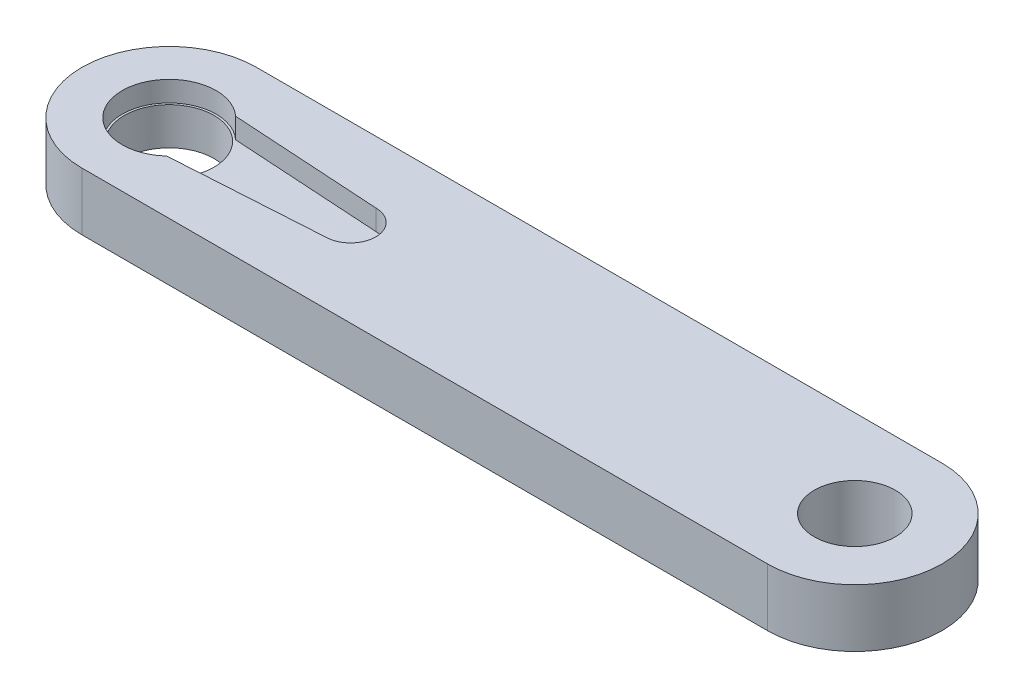
SolidWorks part; units mm, degrees
ref_plane "Front Plane" through (0, 0, 0) normal (0, 0, 1) x (1, 0, 0)
ref_plane "Top Plane" through (0, 0, 0) normal (0, 1, 0) x (1, 0, 0)
ref_plane "Right Plane" through (0, 0, 0) normal (1, 0, 0) x (0, 0, -1)
sketch "Sketch1" plane through (0, 0, 0) normal (0, 1, 0) x (1, 0, 0)
  line L0 (0, 0) -> (62, 0) construction
  line L1 (0, 7) -> (55, 7)
  line L2 (0, -7) -> (55, -7)
  arc A0 (0, 7) -> (0, -7) centre (0, 0) ccw
  arc A2 (55, -7) -> (55, 7) centre (55, 0) ccw
  point P11 (62, 0)
  dimension "D1" = 7
  dimension "D2" = 62
extrude "Boss-Extrude1" add sketch "Sketch1" along normal blind 3
sketch "Sketch2" plane through (0, 0, 0) normal (0, -1, 0) x (1, 0, 0)
  circle A0 centre (0, 0) radius 3.6
  dimension "D1" = 7.2
extrude "Cut-Extrude1" cut sketch "Sketch2" against normal blind 3.95
sketch "Sketch3" plane through (0, 3, 0) normal (0, 1, 0) x (1, 0, 0)
  line L0 (2.49, 2.6) -> (2.49, -2.6) construction
  line L1 (3.6, 0) -> (16.4, 0) construction
  line L2 (2.49, -2.6) -> (14.55, -1.85) construction
  line L3 (14.55, -1.85) -> (14.55, 1.85) construction
  line L4 (14.55, 1.85) -> (2.49, 2.6) construction
  line L5 (14.5554, 2.02) -> (2.5618, 2.7659)
  line L6 (2.5618, -2.7659) -> (14.5554, -2.02)
  line L11 (0, -7) -> (55, -7)
  line L12 (55, 7) -> (0, 7)
  line L13 (0, -7) -> (55, -7)
  line L14 (55, 7) -> (0, 7)
  arc A1 (14.55, -1.85) -> (14.55, 1.85) centre (14.55, 0) ccw construction
  circle A2 centre (0, 0) radius 3.6 construction
  circle A3 centre (14.55, 0) radius 1.85 construction
  circle A4 centre (0, 0) radius 3.575 construction
  arc A5 (2.49, -2.6) -> (2.49, 2.6) centre (0, 0) cw construction
  arc A7 (2.5618, -2.7659) -> (2.5618, 2.7659) centre (0, 0) cw
  arc A8 (14.5554, -2.02) -> (14.5554, 2.02) centre (14.55, 0) ccw
  arc A10 (55, -7) -> (55, 7) centre (55, 0) ccw
  arc A12 (0, 7) -> (0, -7) centre (0, 0) ccw
  arc A14 (0, 7) -> (0, -7) centre (0, 0) ccw
  arc A17 (55, -7) -> (55, 7) centre (55, 0) ccw
  arc A18 (55, -7) -> (55, 7) centre (55, 0) ccw
  point P3 (0, 0)
  point P4 (2.49, 0)
  dimension "D5" = 0
  dimension "D3" = 3.7
  dimension "D6" = 0
  dimension "D1" = 5.2
  dimension "D2" = 12.8
  dimension "D4" = 0.17
extrude "Boss-Extrude2" add sketch "Sketch3" along normal blind 1.64
sketch "Sketch4" plane through (0, 4.64, 0) normal (0, 1, 0) x (1, 0, 0)
  circle A0 centre (55, 0) radius 3.25
  arc A2 (14.5554, -2.02) -> (14.5554, 2.02) centre (14.55, 0) ccw construction
  point P7 (16.57, 0)
  dimension "D1" = 6.5
extrude "Cut-Extrude2" cut sketch "Sketch4" against normal up to surface (4.64 mm away) up to face at (0, 0, -3.6)
